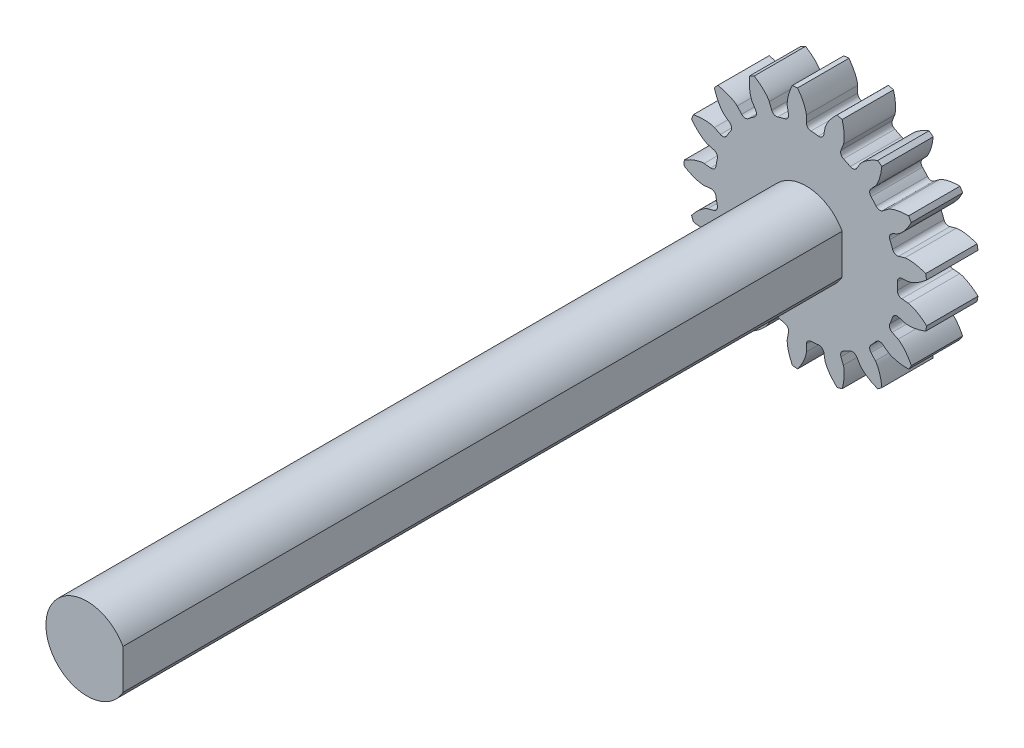
SolidWorks part; units mm, degrees
ref_plane "Front Plane" through (0, 0, 0) normal (0, 0, 1) x (1, 0, 0)
ref_plane "Top Plane" through (0, 0, 0) normal (0, 1, 0) x (1, 0, 0)
ref_plane "Right Plane" through (0, 0, 0) normal (1, 0, 0) x (0, 0, -1)
ref_axis "Gear Axis" through (0, 0, -3.7501) along (0, 0, 1)
sketch "Blank Sketch" plane through (0, 0, 0) normal (0, 0, 1) x (1, 0, 0)
  circle A0 centre (0, 0) radius 11.875
  dimension "OD" = 23.75
extrude "Blank" add sketch "Blank Sketch" along normal blind 5
sketch "Tooth Space Sketch" plane through (0, 0, 0) normal (0, 0, 1) x (1, 0, 0)
  line L0 (9.9424, 0.9134) -> (9.2988, 0.8543)
  line L1 (9.9424, -0.9134) -> (9.2988, -0.8543)
  line L2 (12.7535, 3.1007) -> (12.7535, -3.1007)
  arc A0 (9.2988, 0.8543) -> (8.8676, 0.3619) centre (9.3422, 0.3813) ccw
  arc A1 (8.8676, -0.3619) -> (9.2988, -0.8543) centre (9.3422, -0.3813) ccw
  arc A2 (8.8676, -0.3619) -> (8.8676, 0.3619) centre (0, 0) ccw
  spline S0 degree 4 poles (9.9424, 0.9134) (9.9477, 0.914) (9.9627, 0.9159) (9.9908, 0.9208) (10.0364, 0.9304) (10.094, 0.9451) (10.1679, 0.9668) (10.254, 0.9959) (10.3477, 1.0316) (10.4483, 1.0743) (10.5475, 1.1204) (10.6453, 1.1696) (10.7417, 1.2214) (10.857, 1.2875) (10.9932, 1.3713) (11.1493, 1.4758) (11.3226, 1.602) (11.4947, 1.7386) (11.6604, 1.8795) (11.8233, 2.0291) (11.9776, 2.179) (12.1329, 2.3418) (12.2737, 2.4958) (12.4257, 2.676) (12.5467, 2.8236) (12.6999, 3.0262) (12.7884, 3.1482) (12.8897, 3.2936) (12.9335, 3.3596) (12.9605, 3.4002) knots 0 0 0 0 0 0.005377 0.015084 0.028532 0.04661 0.064855 0.092111 0.119476 0.146842 0.174209 0.201575 0.228941 0.256307 0.307035 0.361767 0.4165 0.471232 0.525964 0.580697 0.635429 0.690161 0.744894 0.799626 0.854358 0.909091 0.954545 1 1 1 1 1 construction
  spline S1 degree 4 poles (9.9424, 0.9134) (9.9477, 0.914) (9.9627, 0.9159) (9.9908, 0.9208) (10.0364, 0.9304) (10.094, 0.9451) (10.1679, 0.9668) (10.254, 0.9959) (10.3477, 1.0316) (10.4483, 1.0743) (10.5475, 1.1204) (10.6453, 1.1696) (10.7417, 1.2214) (10.857, 1.2875) (10.9932, 1.3713) (11.1493, 1.4758) (11.3226, 1.602) (11.4947, 1.7386) (11.6604, 1.8795) (11.8233, 2.0291) (11.9776, 2.179) (12.1329, 2.3418) (12.2737, 2.4958) (12.4257, 2.676) (12.5467, 2.8236) (12.6667, 2.9823) (12.7243, 3.0604) (12.7535, 3.1007) knots 0 0 0 0 0 0.005377 0.015084 0.028532 0.04661 0.064855 0.092111 0.119476 0.146842 0.174209 0.201575 0.228941 0.256307 0.307035 0.361767 0.4165 0.471232 0.525964 0.580697 0.635429 0.690161 0.744894 0.799626 0.854358 0.909091 0.909091 0.909091 0.909091 0.909091
  spline S2 degree 4 poles (9.9424, -0.9134) (9.9477, -0.914) (9.9627, -0.9159) (9.9908, -0.9208) (10.0364, -0.9304) (10.094, -0.9451) (10.1679, -0.9668) (10.254, -0.9959) (10.3477, -1.0316) (10.4483, -1.0743) (10.5475, -1.1204) (10.6453, -1.1696) (10.7417, -1.2214) (10.857, -1.2875) (10.9932, -1.3713) (11.1493, -1.4758) (11.3226, -1.602) (11.4947, -1.7386) (11.6604, -1.8795) (11.8233, -2.0291) (11.9776, -2.179) (12.1329, -2.3418) (12.2737, -2.4958) (12.4257, -2.676) (12.5467, -2.8236) (12.6999, -3.0262) (12.7884, -3.1482) (12.8897, -3.2936) (12.9335, -3.3596) (12.9605, -3.4002) knots 0 0 0 0 0 0.005377 0.015084 0.028532 0.04661 0.064855 0.092111 0.119476 0.146842 0.174209 0.201575 0.228941 0.256307 0.307035 0.361767 0.4165 0.471232 0.525964 0.580697 0.635429 0.690161 0.744894 0.799626 0.854358 0.909091 0.954545 1 1 1 1 1 construction
  spline S3 degree 4 poles (9.9424, -0.9134) (9.9477, -0.914) (9.9627, -0.9159) (9.9908, -0.9208) (10.0364, -0.9304) (10.094, -0.9451) (10.1679, -0.9668) (10.254, -0.9959) (10.3477, -1.0316) (10.4483, -1.0743) (10.5475, -1.1204) (10.6453, -1.1696) (10.7417, -1.2214) (10.857, -1.2875) (10.9932, -1.3713) (11.1493, -1.4758) (11.3226, -1.602) (11.4947, -1.7386) (11.6604, -1.8795) (11.8233, -2.0291) (11.9776, -2.179) (12.1329, -2.3418) (12.2737, -2.4958) (12.4257, -2.676) (12.5467, -2.8236) (12.6667, -2.9823) (12.7243, -3.0604) (12.7535, -3.1007) knots 0 0 0 0 0 0.005377 0.015084 0.028532 0.04661 0.064855 0.092111 0.119476 0.146842 0.174209 0.201575 0.228941 0.256307 0.307035 0.361767 0.4165 0.471232 0.525964 0.580697 0.635429 0.690161 0.744894 0.799626 0.854358 0.909091 0.909091 0.909091 0.909091 0.909091
  dimension "Root" = 8.875
  dimension "Fillet" = 0.475
extrude "Tooth Space" cut sketch "Tooth Space Sketch" against normal through all both and the other way through all both
pattern_circular "Teeth" count 17 over 360 about axis through (0, 0, -3.7501) along (0, 0, 1) of "Tooth Space"
sketch "Bore Sketch" plane through (0, 0, 0) normal (0, 0, 1) x (1, 0, 0)
  circle A0 centre (0, 0) radius 4
  dimension "Bore" = 8
extrude "Bore" cut sketch "Bore Sketch" against normal through all both and the other way through all both
sketch "Sketch1" plane through (0, 0, 0) normal (0, 0, -1) x (-1, 0, 0)
  circle A1 centre (0, 0) radius 4 construction
  circle A2 centre (0, 0) radius 4
extrude "Boss-Extrude1" add sketch "Sketch1" against normal blind 75
sketch "Sketch2" plane through (0, 0, 5) normal (0, 0, 1) x (1, 0, 0)
  line L0 (3.5, 1.9365) -> (3.5, -1.9365)
  circle A0 centre (0, 0) radius 4
  arc A1 (3.5, -1.9365) -> (3.5, 1.9365) centre (0, 0) ccw
  arc A2 (3.5, 1.9365) -> (3.5, -1.9365) centre (0, 0) ccw construction
  dimension "D1" = 3.5
extrude "Cut-Extrude1" cut sketch "Sketch2" along normal up to surface (70 mm away) up to face at (-4, 0, 75)
equation "\"No. of Teeth\"= 17"
equation "\"Module\"= 1.25"
equation "\"Bore Diameter\"= 8"
equation "\"Pressure Angle\"= 20"
equation "\"Outer Diameter\"= ( \"No. of Teeth\" + 2 ) * \"Module\""
equation "\"Pitch Diameter\"= \"No. of Teeth\" * \"Module\""
equation "\"Backlash\"= IIF ( \"Module\" <= 1 , 0.3 * \"Module\" , 0.3 )"
equation "\"Arc Length\"= ( ( \"Module\" * pi ) / 2 + \"Backlash\" )"
equation "\"Fillet Radius\"= 0.38 * \"Module\""
equation "\"Tooth Depth\"= IIF ( \"Module\" <= 1.25 , \"Module\" * 2.4 , \"Module\" * 2.25 )"
equation "\"Face Width\"= 5"
equation "\"Root Diameter\"= \"Outer Diameter\" - 2 * \"Tooth Depth\""
equation "\"Base Diameter\"= \"Pitch Diameter\" * cos ( \"Pressure Angle\" )"
equation "\"Base Radius\"= \"Base Diameter\" / 2"
equation "\"Tooth Thickness\"= \"Module\" * pi - \"Arc Length\""
equation "\"Half Space Angle\"= ( \"Arc Length\" / \"Pitch Diameter\" ) * 180 / pi"
equation "\"Involute Fn\"= tan ( \"Pressure Angle\" ) - \"Pressure Angle\" * pi / 180"
equation "\"Flank Offset\"= \"Arc Length\" / \"Pitch Diameter\" - \"Involute Fn\""
equation "\"Tip Cap Diameter\"= \"Outer Diameter\" + 2 * \"Module\""
equation "\"Flank Start Diameter\"= IIF ( \"Base Diameter\" >= ( \"Root Diameter\" + 3 * \"Fillet Radius\" ) , \"Base Diameter\" , \"Root Diameter\" + 3 * \"Fillet Radius\" )"
equation "\"Involute t1\"= ( abs ( ( \"Flank Start Diameter\" / \"Base Diameter\" ) ^ 2 - 1 ) ) ^ 0.5"
equation "\"Involute t2\"= ( abs ( ( \"Tip Cap Diameter\" / \"Base Diameter\" ) ^ 2 - 1 ) ) ^ 0.5"
equation "\"Flank Arc Radius\"= ( \"Pitch Diameter\" / 2 ) * sin ( \"Pressure Angle\" )"
equation "\"Flank Centre Angle\"= \"Half Space Angle\" + \"Pressure Angle\""
equation "\"OD@Blank Sketch\"= \"Outer Diameter\""
equation "\"Width@Blank\"= \"Face Width\""
equation "\"Root@Tooth Space Sketch\"= \"Root Diameter\" / 2"
equation "\"Fillet@Tooth Space Sketch\"= \"Fillet Radius\""
equation "\"Count@Teeth\"= \"No. of Teeth\""
equation "\"Bore@Bore Sketch\"= \"Bore Diameter\""
